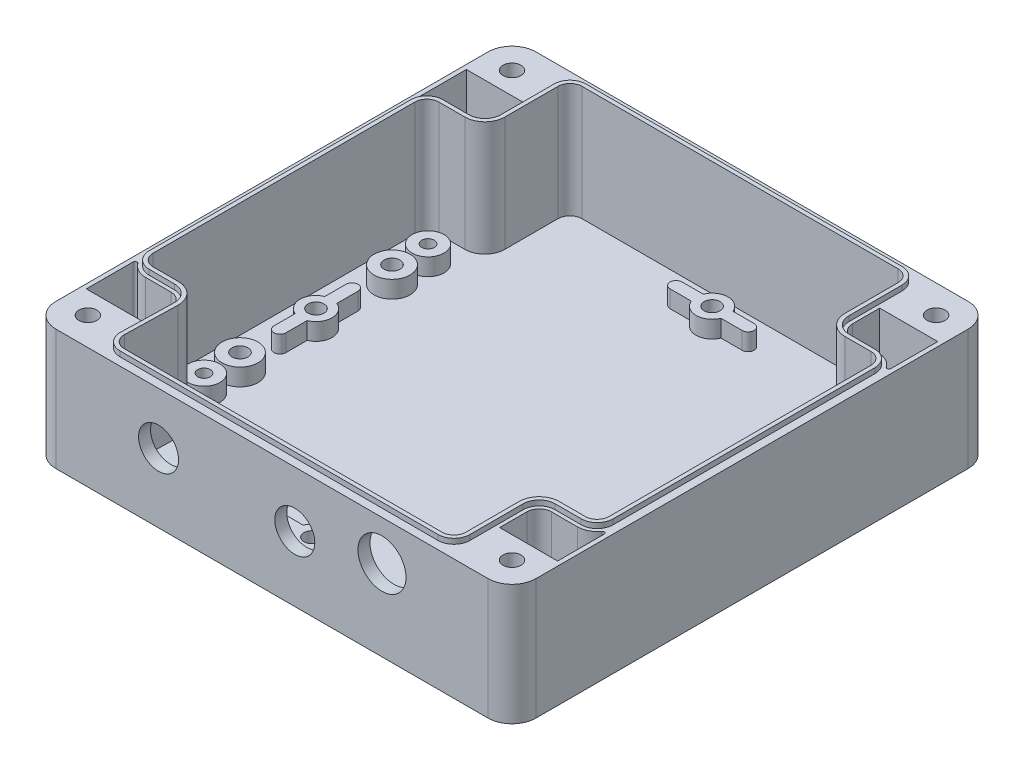
SolidWorks part; units mm, degrees
other "陽光" [suppressed]
ref_plane "前基準面" through (0, 0, 0) normal (0, 0, 1) x (1, 0, 0)
ref_plane "上基準面" through (0, 0, 0) normal (0, 1, 0) x (1, 0, 0)
ref_plane "右基準面" through (0, 0, 0) normal (1, 0, 0) x (0, 0, -1)
sketch "草圖1" plane through (0, 0, 0) normal (0, 1, 0) x (1, 0, 0)
  line L1 (6.3409, 120.3409) -> (114.3409, 120.3409)
  line L2 (0.3409, 114.3409) -> (0.3409, 6.3409)
  line L3 (6.3409, 0.3409) -> (114.3409, 0.3409)
  line L4 (120.3409, 114.3409) -> (120.3409, 6.3409)
  circle A0 centre (7.3409, 113.3409) radius 2.25
  circle A1 centre (7.3409, 103.3409) radius 2.25
  circle A2 centre (113.3409, 113.3409) radius 2.25
  circle A3 centre (113.3409, 103.3409) radius 2.25
  circle A4 centre (7.3409, 17.3409) radius 2.25
  circle A5 centre (7.3409, 7.3409) radius 2.25
  circle A6 centre (113.3409, 17.3409) radius 2.25
  circle A7 centre (113.3409, 7.3409) radius 2.25
  arc A8 (114.3409, 120.3409) -> (120.3409, 114.3409) centre (114.3409, 114.3409) cw
  arc A9 (120.3409, 6.3409) -> (114.3409, 0.3409) centre (114.3409, 6.3409) cw
  arc A10 (6.3409, 0.3409) -> (0.3409, 6.3409) centre (6.3409, 6.3409) cw
  arc A11 (0.3409, 114.3409) -> (6.3409, 120.3409) centre (6.3409, 114.3409) cw
  point P37 (120.3409, 120.3409)
  point P42 (0.3409, 0.3409)
  point P45 (0.3409, 120.3409)
  dimension "D3" = 106
  dimension "D4" = 7
  dimension "D7" = 7
  dimension "D13" = 6
  dimension "D5" = 10
  dimension "D6" = 106
  dimension "D9" = 10
  dimension "D2" = 120
  dimension "D8" = 7
  dimension "D10" = 120
  dimension "D11" = 86
  dimension "D12" = 7
extrude "填料-伸長1" add sketch "草圖1" along normal blind 31.5
sketch "草圖2" plane through (0, 31.5, 0) normal (0, 1, 0) x (1, 0, 0)
  line L1 (15.9409, 101.0538) -> (15.9409, 107.8409)
  line L21 (6.3409, 97.9538) -> (12.8409, 97.9538)
  line L23 (6.3281, 22.7581) -> (12.7279, 22.7414)
  line L25 (15.8189, 19.567) -> (15.6575, 12.8409)
  line L28 (6.3409, 96.0538) -> (12.8409, 96.0538)
  line L29 (0.3409, 114.3409) -> (0.3409, 6.3409) construction
  line L32 (17.8409, 101.0538) -> (17.8409, 114.3409)
  line L34 (114.3409, 120.3409) -> (6.3409, 120.3409) construction
  line L43 (99.8409, 117.3409) -> (20.8409, 117.3409)
  line L44 (3.3409, 93.0538) -> (3.3409, 27.6581)
  line L45 (20.403, 3.3409) -> (99.8409, 3.3409)
  line L46 (117.3409, 27.628) -> (117.3409, 93.0538)
  line L47 (0.3409, 60.3409) -> (120.3409, 60.3409) construction
  line L48 (104.7409, 19.628) -> (104.7409, 12.8409)
  line L49 (120.3409, 6.3409) -> (120.3409, 114.3409) construction
  line L50 (60.3409, 120.3409) -> (60.3409, 0.3409) construction
  line L51 (114.3409, 22.728) -> (107.8409, 22.728)
  line L52 (6.3409, 0.3409) -> (114.3409, 0.3409) construction
  line L53 (17.7184, 19.5214) -> (17.4038, 6.4129)
  line L54 (6.3331, 24.6581) -> (12.7329, 24.6414)
  line L55 (102.8409, 19.628) -> (102.8409, 6.3409)
  line L56 (114.3409, 24.628) -> (107.8409, 24.628)
  line L57 (114.3409, 96.0538) -> (107.8409, 96.0538)
  line L58 (102.8409, 101.0538) -> (102.8409, 114.3409)
  line L60 (114.3409, 97.9538) -> (107.8409, 97.9538)
  line L61 (104.7409, 101.0538) -> (104.7409, 107.8409)
  line L62 (1.4409, 96.1843) -> (1.4409, 107.8409)
  line L63 (1.4409, 107.8409) -> (15.9409, 107.8409)
  line L65 (1.4409, 24.5276) -> (1.4409, 12.8409)
  line L66 (1.4409, 12.8409) -> (15.6575, 12.8409)
  line L67 (119.2409, 96.1843) -> (119.2409, 107.8409)
  line L68 (119.2409, 107.8409) -> (104.7409, 107.8409)
  line L69 (119.2409, 24.4975) -> (119.2409, 12.8409)
  line L70 (119.2409, 12.8409) -> (104.7409, 12.8409)
  arc A12 (107.8409, 96.0538) -> (102.8409, 101.0538) centre (107.8409, 101.0538) cw
  arc A13 (12.8409, 96.0538) -> (17.8409, 101.0538) centre (12.8409, 101.0538) ccw
  arc A14 (102.8409, 19.628) -> (107.8409, 24.628) centre (107.8409, 19.628) cw
  arc A30 (17.7184, 19.5214) -> (12.7329, 24.6414) centre (12.7198, 19.6414) ccw
  arc A32 (102.8409, 6.3409) -> (99.8409, 3.3409) centre (99.8409, 6.3409) cw
  arc A34 (114.3409, 24.628) -> (117.3409, 27.628) centre (114.3409, 27.628) ccw
  arc A35 (114.3409, 96.0538) -> (117.3409, 93.0538) centre (114.3409, 93.0538) cw
  arc A36 (102.8409, 114.3409) -> (99.8409, 117.3409) centre (99.8409, 114.3409) ccw
  arc A37 (17.8409, 114.3409) -> (20.8409, 117.3409) centre (20.8409, 114.3409) cw
  arc A39 (6.3409, 96.0538) -> (3.3409, 93.0538) centre (6.3409, 93.0538) ccw
  arc A40 (6.3331, 24.6581) -> (3.3409, 27.6581) centre (6.3409, 27.6581) cw
  arc A41 (17.4038, 6.4129) -> (20.403, 3.3409) centre (20.403, 6.3409) ccw
  arc A43 (1.4409, 24.5276) -> (2.3483, 24.8175) centre (1.9409, 24.5276) cw
  arc A45 (2.3483, 95.8944) -> (1.4409, 96.1843) centre (1.9409, 96.1843) cw
  arc A51 (12.8409, 97.9538) -> (15.9409, 101.0538) centre (12.8409, 101.0538) ccw
  arc A52 (6.3409, 97.9538) -> (2.3483, 95.8944) centre (6.3409, 93.0538) ccw
  arc A53 (6.3281, 22.7581) -> (2.3483, 24.8175) centre (6.3409, 27.6581) cw
  arc A54 (15.8189, 19.567) -> (12.7279, 22.7414) centre (12.7198, 19.6414) ccw
  arc A57 (104.7409, 19.628) -> (107.8409, 22.728) centre (107.8409, 19.628) cw
  arc A58 (114.3409, 22.728) -> (118.3335, 24.7874) centre (114.3409, 27.628) ccw
  arc A59 (114.3409, 97.9538) -> (118.3335, 95.8944) centre (114.3409, 93.0538) cw
  arc A60 (107.8409, 97.9538) -> (104.7409, 101.0538) centre (107.8409, 101.0538) cw
  arc A67 (119.2409, 96.1843) -> (118.3335, 95.8944) centre (118.7409, 96.1843) cw
  arc A69 (118.3335, 24.7874) -> (119.2409, 24.4975) centre (118.7409, 24.4975) cw
  point P41 (102.8409, 96.0538)
  point P44 (17.8409, 96.0538)
  point P47 (102.8409, 24.628)
  point P50 (17.8409, 24.628)
  point P57 (104.8409, 17.8409)
  point P59 (110.2409, 20.8409)
  point P60 (110.2409, 24.0409)
  point P61 (113.4409, 24.0409)
  point P62 (113.4409, 65.9246)
  point P63 (110.2409, 65.9246)
  point P64 (110.2409, 69.1246)
  point P67 (104.8409, 72.1246)
  point P68 (104.8409, 85.2409)
  point P69 (101.6409, 85.2409)
  point P70 (101.6409, 88.4409)
  point P73 (10.8409, 85.2409)
  point P74 (10.8409, 72.8409)
  point P77 (5.4409, 69.8409)
  point P78 (5.4409, 66.6409)
  point P79 (2.2409, 66.6409)
  point P80 (2.2409, 24.0409)
  point P81 (5.4409, 24.0409)
  point P82 (5.4409, 20.8409)
  point P85 (10.5331, 17.8409)
  point P86 (10.5331, 5.4409)
  point P88 (99.8409, 119.2409)
  point P89 (20.8409, 119.2409)
  point P91 (104.8409, 5.4409)
  point P92 (15.9409, 114.3409)
  point P98 (1.4409, 93.0538)
  point P105 (15.5044, 6.4585)
  point P107 (20.403, 1.4409)
  point P108 (99.8409, 1.4409)
  point P110 (104.7409, 6.3409)
  point P116 (119.2409, 27.628)
  point P117 (119.2409, 93.0538)
  point P123 (104.7409, 114.3409)
extrude "除料-伸長1" cut sketch "草圖2" against normal blind 28.65
sketch "草圖3" plane through (0, 31.5, 0) normal (0, 1, 0) x (1, 0, 0)
  line L24 (103.8409, 101.0538) -> (103.8409, 114.3409)
  line L25 (99.8409, 118.3409) -> (20.8409, 118.3409)
  line L26 (16.8409, 114.3409) -> (16.8409, 101.0538)
  line L27 (12.8409, 97.0538) -> (6.3409, 97.0538)
  line L28 (2.3409, 93.0538) -> (2.3409, 27.6581)
  line L29 (6.3304, 23.6581) -> (12.7303, 23.6414)
  line L30 (16.7187, 19.5454) -> (16.4041, 6.4369)
  line L31 (20.403, 2.3409) -> (99.8409, 2.3409)
  line L32 (103.8409, 6.3409) -> (103.8409, 19.628)
  line L33 (107.8409, 23.628) -> (114.3409, 23.628)
  line L34 (118.3409, 27.628) -> (118.3409, 93.0538)
  line L35 (114.3409, 97.0538) -> (107.8409, 97.0538)
  line L36 (103.8409, 101.0538) -> (103.8409, 114.3409)
  line L37 (99.8409, 118.3409) -> (20.8409, 118.3409)
  line L38 (16.8409, 114.3409) -> (16.8409, 101.0538)
  line L39 (12.8409, 97.0538) -> (6.3409, 97.0538)
  line L40 (2.3409, 93.0538) -> (2.3409, 27.6581)
  line L41 (6.3304, 23.6581) -> (12.7303, 23.6414)
  line L42 (16.7187, 19.5454) -> (16.4041, 6.4369)
  line L43 (20.403, 2.3409) -> (99.8409, 2.3409)
  line L44 (103.8409, 6.3409) -> (103.8409, 19.628)
  line L45 (107.8409, 23.628) -> (114.3409, 23.628)
  line L46 (118.3409, 27.628) -> (118.3409, 93.0538)
  line L47 (114.3409, 97.0538) -> (107.8409, 97.0538)
  line L48 (6.3409, 0.3409) -> (114.3409, 0.3409)
  line L49 (120.3409, 6.3409) -> (120.3409, 114.3409)
  line L50 (0.3409, 114.3409) -> (0.3409, 6.3409)
  line L51 (114.3409, 120.3409) -> (6.3409, 120.3409)
  line L52 (6.3409, 0.3409) -> (114.3409, 0.3409)
  line L53 (120.3409, 6.3409) -> (120.3409, 114.3409)
  line L54 (0.3409, 114.3409) -> (0.3409, 6.3409)
  line L55 (114.3409, 120.3409) -> (6.3409, 120.3409)
  arc A20 (0.3409, 6.3409) -> (6.3409, 0.3409) centre (6.3409, 6.3409) ccw
  arc A21 (114.3409, 0.3409) -> (120.3409, 6.3409) centre (114.3409, 6.3409) ccw
  arc A22 (120.3409, 114.3409) -> (114.3409, 120.3409) centre (114.3409, 114.3409) ccw
  arc A23 (6.3409, 120.3409) -> (0.3409, 114.3409) centre (6.3409, 114.3409) ccw
  arc A24 (103.8409, 101.0538) -> (107.8409, 97.0538) centre (107.8409, 101.0538) ccw
  arc A25 (103.8409, 114.3409) -> (99.8409, 118.3409) centre (99.8409, 114.3409) ccw
  arc A26 (20.8409, 118.3409) -> (16.8409, 114.3409) centre (20.8409, 114.3409) ccw
  arc A27 (12.8409, 97.0538) -> (16.8409, 101.0538) centre (12.8409, 101.0538) ccw
  arc A28 (6.3409, 97.0538) -> (2.3409, 93.0538) centre (6.3409, 93.0538) ccw
  arc A29 (2.3409, 27.6581) -> (6.3304, 23.6581) centre (6.3409, 27.6581) ccw
  arc A30 (16.7187, 19.5454) -> (12.7303, 23.6414) centre (12.7198, 19.6414) ccw
  arc A31 (16.4041, 6.4369) -> (20.403, 2.3409) centre (20.403, 6.3409) ccw
  arc A32 (99.8409, 2.3409) -> (103.8409, 6.3409) centre (99.8409, 6.3409) ccw
  arc A33 (107.8409, 23.628) -> (103.8409, 19.628) centre (107.8409, 19.628) ccw
  arc A34 (114.3409, 23.628) -> (118.3409, 27.628) centre (114.3409, 27.628) ccw
  arc A35 (118.3409, 93.0538) -> (114.3409, 97.0538) centre (114.3409, 93.0538) ccw
  arc A36 (103.8409, 101.0538) -> (107.8409, 97.0538) centre (107.8409, 101.0538) ccw
  arc A37 (103.8409, 114.3409) -> (99.8409, 118.3409) centre (99.8409, 114.3409) ccw
  arc A38 (20.8409, 118.3409) -> (16.8409, 114.3409) centre (20.8409, 114.3409) ccw
  arc A39 (12.8409, 97.0538) -> (16.8409, 101.0538) centre (12.8409, 101.0538) ccw
  arc A40 (6.3409, 97.0538) -> (2.3409, 93.0538) centre (6.3409, 93.0538) ccw
  arc A41 (2.3409, 27.6581) -> (6.3304, 23.6581) centre (6.3409, 27.6581) ccw
  arc A42 (16.7187, 19.5454) -> (12.7303, 23.6414) centre (12.7198, 19.6414) ccw
  arc A43 (16.4041, 6.4369) -> (20.403, 2.3409) centre (20.403, 6.3409) ccw
  arc A44 (99.8409, 2.3409) -> (103.8409, 6.3409) centre (99.8409, 6.3409) ccw
  arc A45 (107.8409, 23.628) -> (103.8409, 19.628) centre (107.8409, 19.628) ccw
  arc A46 (114.3409, 23.628) -> (118.3409, 27.628) centre (114.3409, 27.628) ccw
  arc A47 (118.3409, 93.0538) -> (114.3409, 97.0538) centre (114.3409, 93.0538) ccw
  arc A48 (0.3409, 6.3409) -> (6.3409, 0.3409) centre (6.3409, 6.3409) ccw
  arc A49 (114.3409, 0.3409) -> (120.3409, 6.3409) centre (114.3409, 6.3409) ccw
  arc A50 (120.3409, 114.3409) -> (114.3409, 120.3409) centre (114.3409, 114.3409) ccw
  arc A51 (6.3409, 120.3409) -> (0.3409, 114.3409) centre (6.3409, 114.3409) ccw
  dimension "D1" = 1
  dimension "D2" = 0
extrude "除料-伸長2" cut sketch "草圖3" against normal blind 1.3
sketch "草圖4" plane through (0, 2.85, 0) normal (0, 1, 0) x (1, 0, 0)
  line L0 (60.3409, 117.3409) -> (60.3409, 3.3409) construction
  line L5 (99.8409, 117.3409) -> (20.8409, 117.3409) construction
  line L6 (20.403, 3.3409) -> (99.8409, 3.3409) construction
  line L7 (3.3409, 60.356) -> (117.3409, 60.356) construction
  line L8 (3.3409, 93.0538) -> (3.3409, 27.6581) construction
  line L9 (117.3409, 27.628) -> (117.3409, 93.0538) construction
  line L10 (64.049, 111.856) -> (69.3409, 111.856)
  line L11 (64.049, 108.856) -> (69.3409, 108.856)
  line L12 (107.8409, 64.064) -> (107.8409, 69.356)
  line L13 (110.8409, 64.064) -> (110.8409, 69.356)
  line L14 (51.3409, 10.356) -> (69.3409, 10.356) construction
  line L15 (51.3409, 11.856) -> (56.6328, 11.856)
  line L16 (51.3409, 8.856) -> (56.6328, 8.856)
  line L17 (11.3409, 51.356) -> (11.3409, 69.356) construction
  line L18 (9.8409, 51.356) -> (9.8409, 56.6479)
  line L19 (12.8409, 51.356) -> (12.8409, 56.6479)
  line L20 (109.3409, 51.356) -> (109.3409, 69.356) construction
  line L21 (107.8409, 51.356) -> (107.8409, 56.6479)
  line L22 (110.8409, 51.356) -> (110.8409, 56.6479)
  line L23 (51.3409, 110.356) -> (69.3409, 110.356) construction
  line L24 (51.3409, 111.856) -> (56.6328, 111.856)
  line L25 (51.3409, 108.856) -> (56.6328, 108.856)
  line L26 (12.8409, 64.064) -> (12.8409, 69.356)
  line L27 (9.8409, 64.064) -> (9.8409, 69.356)
  line L28 (64.049, 8.856) -> (69.3409, 8.856)
  line L29 (64.049, 11.856) -> (69.3409, 11.856)
  arc A0 (64.049, 111.856) -> (56.6328, 111.856) centre (60.3409, 110.356) ccw
  arc A1 (64.049, 11.856) -> (56.6328, 11.856) centre (60.3409, 10.356) ccw
  arc A2 (9.8409, 64.064) -> (9.8409, 56.6479) centre (11.3409, 60.356) ccw
  arc A3 (107.8409, 64.064) -> (107.8409, 56.6479) centre (109.3409, 60.356) ccw
  arc A4 (51.3409, 11.856) -> (51.3409, 8.856) centre (51.3409, 10.356) ccw
  arc A5 (69.3409, 8.856) -> (69.3409, 11.856) centre (69.3409, 10.356) ccw
  arc A6 (9.8409, 51.356) -> (12.8409, 51.356) centre (11.3409, 51.356) ccw
  arc A7 (12.8409, 69.356) -> (9.8409, 69.356) centre (11.3409, 69.356) ccw
  arc A8 (107.8409, 51.356) -> (110.8409, 51.356) centre (109.3409, 51.356) ccw
  arc A9 (110.8409, 69.356) -> (107.8409, 69.356) centre (109.3409, 69.356) ccw
  arc A10 (51.3409, 111.856) -> (51.3409, 108.856) centre (51.3409, 110.356) ccw
  arc A11 (69.3409, 108.856) -> (69.3409, 111.856) centre (69.3409, 110.356) ccw
  arc A12 (56.6328, 108.856) -> (64.049, 108.856) centre (60.3409, 110.356) ccw
  arc A13 (110.8409, 56.6479) -> (110.8409, 64.064) centre (109.3409, 60.356) ccw
  arc A14 (12.8409, 56.6479) -> (12.8409, 64.064) centre (11.3409, 60.356) ccw
  arc A15 (56.6328, 8.856) -> (64.049, 8.856) centre (60.3409, 10.356) ccw
  circle A16 centre (60.3409, 10.356) radius 2
  circle A17 centre (109.3409, 60.356) radius 2
  circle A18 centre (60.3409, 110.356) radius 2
  circle A19 centre (11.3409, 60.356) radius 2
  circle A20 centre (11.3409, 79.356) radius 4.5
  circle A21 centre (11.3409, 88.356) radius 4
  circle A22 centre (11.3409, 79.356) radius 2
  circle A23 centre (11.3409, 41.356) radius 4.5
  circle A24 centre (11.3409, 32.356) radius 4
  circle A25 centre (11.3409, 41.356) radius 2
  circle A26 centre (109.3409, 88.356) radius 4
  circle A27 centre (109.3409, 79.356) radius 2
  circle A28 centre (109.3409, 79.356) radius 4.5
  circle A29 centre (109.3409, 41.356) radius 2
  circle A30 centre (109.3409, 41.356) radius 4.5
  circle A31 centre (109.3409, 32.356) radius 4
  point P23 (60.3409, 110.356)
  point P26 (109.3409, 60.356)
  point P29 (11.3409, 60.356)
  point P32 (60.3409, 10.356)
  point P33 (60.3409, 10.356)
  point P39 (11.3409, 60.356)
  point P45 (109.3409, 60.356)
  point P51 (60.3409, 110.356)
  dimension "D1" = 8
  dimension "D2" = 8
  dimension "D3" = 100
  dimension "D5" = 8
  dimension "D6" = 8
  dimension "D7" = 98
  dimension "D9" = 4
  dimension "D10" = 4
  dimension "D11" = 4
  dimension "D12" = 4
  dimension "D13" = 9
  dimension "D14" = 8
  dimension "D15" = 28
  dimension "D16" = 19
  dimension "D17" = 4
  dimension "D4" = 50
  dimension "D8" = 49
extrude "填料-伸長5" add sketch "草圖4" along normal blind 4.3
hole_wizard "M3 螺旋的螺孔鑽1" positions "草圖5" profile "草圖6" hole size "M3x0.5" standard "Ansi Metric"
sketch "草圖5" plane through (0, 7.15, 0) normal (0, 1, 0) x (1, 0, 0)
  point P0 (11.3409, 88.356)
  point P3 (11.3409, 32.356)
  point P6 (109.3409, 32.356)
  point P9 (109.3409, 88.356)
sketch "草圖6" plane through (11.3409, 7.15, -88.356) normal (1, 0, 0) x (0, 0, 1)
  line L0 (0, 0) -> (0, 4.9464)
  line L1 (0, 4.9464) -> (1.575, 4)
  line L2 (1.575, 4) -> (1.575, 0)
  line L5 (1.575, 0) -> (0, 0)
  line L10 (0, 4.9464) -> (-1.575, 4) construction
  line L11 (0, -6.35) -> (0, 107.95) construction
  dimension "鑽孔直徑" = 3.15
  dimension "鑽孔深度" = 4
  dimension "導頭角度" = 118
sketch "草圖7" plane through (0, 0, -0.3409) normal (0, 0, 1) x (1, 0, 0)
  circle A0 centre (32.0021, 17.25) radius 5
  circle A1 centre (66.0521, 16.3) radius 5
  circle A2 centre (87.8409, 20.2) radius 6
  dimension "D1" = 10
  dimension "D2" = 10
  dimension "D3" = 12
extrude "除料-伸長3" cut sketch "草圖7" against normal up to next
